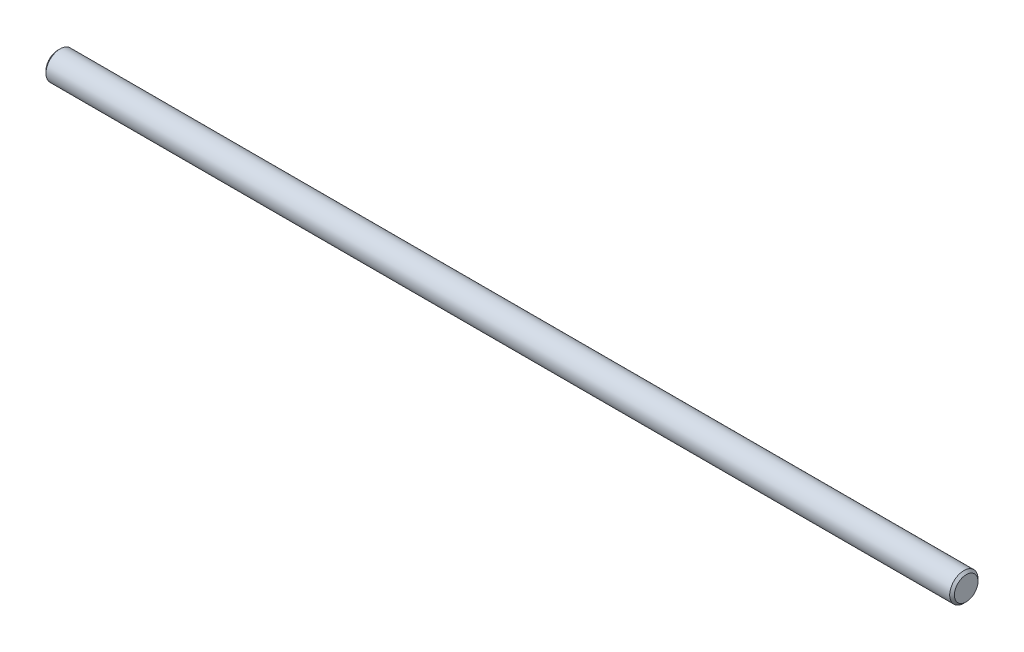
SolidWorks part; units mm, degrees
ref_plane "Front Plane" through (0, 0, 0) normal (0, 0, 1) x (1, 0, 0)
ref_plane "Top Plane" through (0, 0, 0) normal (0, 1, 0) x (1, 0, 0)
ref_plane "Right Plane" through (0, 0, 0) normal (1, 0, 0) x (0, 0, -1)
sketch "Sketch1" plane through (0, 0, 0) normal (1, 0, 0) x (0, 0, -1)
  circle A0 centre (0, 0) radius 6
  dimension "D1" = 12
extrude "Boss-Extrude1" add sketch "Sketch1" along normal mid plane 385
chamfer "Chamfer1" distance 1 angle 45 2 edges at (192.5, 0, -6) (-192.5, 0, -6)
